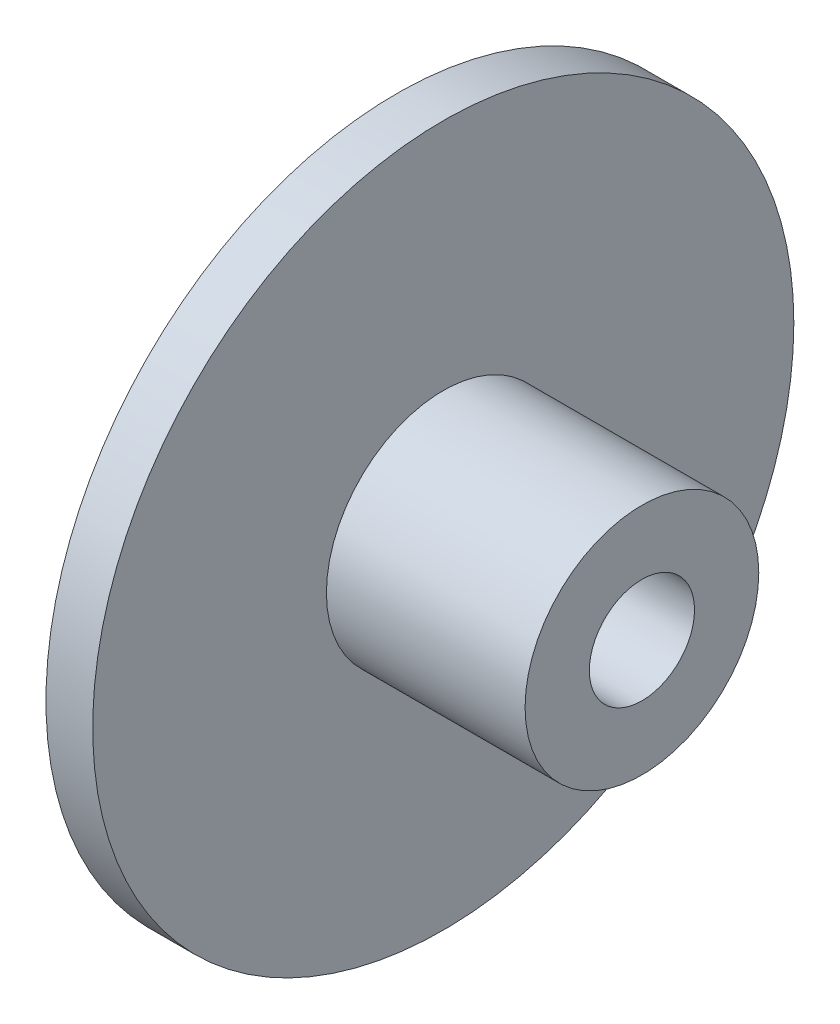
SolidWorks part; units mm, degrees
ref_plane "Alzado" through (0, 0, 0) normal (0, 0, 1) x (1, 0, 0)
ref_plane "Planta" through (0, 0, 0) normal (0, 1, 0) x (1, 0, 0)
ref_plane "Vista lateral" through (0, 0, 0) normal (1, 0, 0) x (0, 0, -1)
sketch "Croquis1" plane through (0, 0, 0) normal (1, 0, 0) x (0, 0, -1)
  circle A0 centre (0, 0) radius 2.25
  circle A1 centre (0, 0) radius 15
  dimension "D1" = 4.5
  dimension "D2" = 30
extrude "Saliente-Extruir1" add sketch "Croquis1" along normal blind 2
sketch "Croquis3" plane through (2, 0, 0) normal (1, 0, 0) x (0, 0, -1)
  circle A0 centre (0, 0) radius 2.25 construction
  circle A1 centre (0, 0) radius 2.25
  circle A2 centre (0, 0) radius 5
  dimension "D1" = 10
extrude "Saliente-Extruir2" add sketch "Croquis3" along normal blind 8.5
sketch "Croquis4" plane through (0, 0, 0) normal (-1, 0, 0) x (0, 0, 1)
  circle A0 centre (0, 0) radius 3.75
  dimension "D1" = 7.5
extrude "Cortar-Extruir1" cut sketch "Croquis4" against normal blind 4
